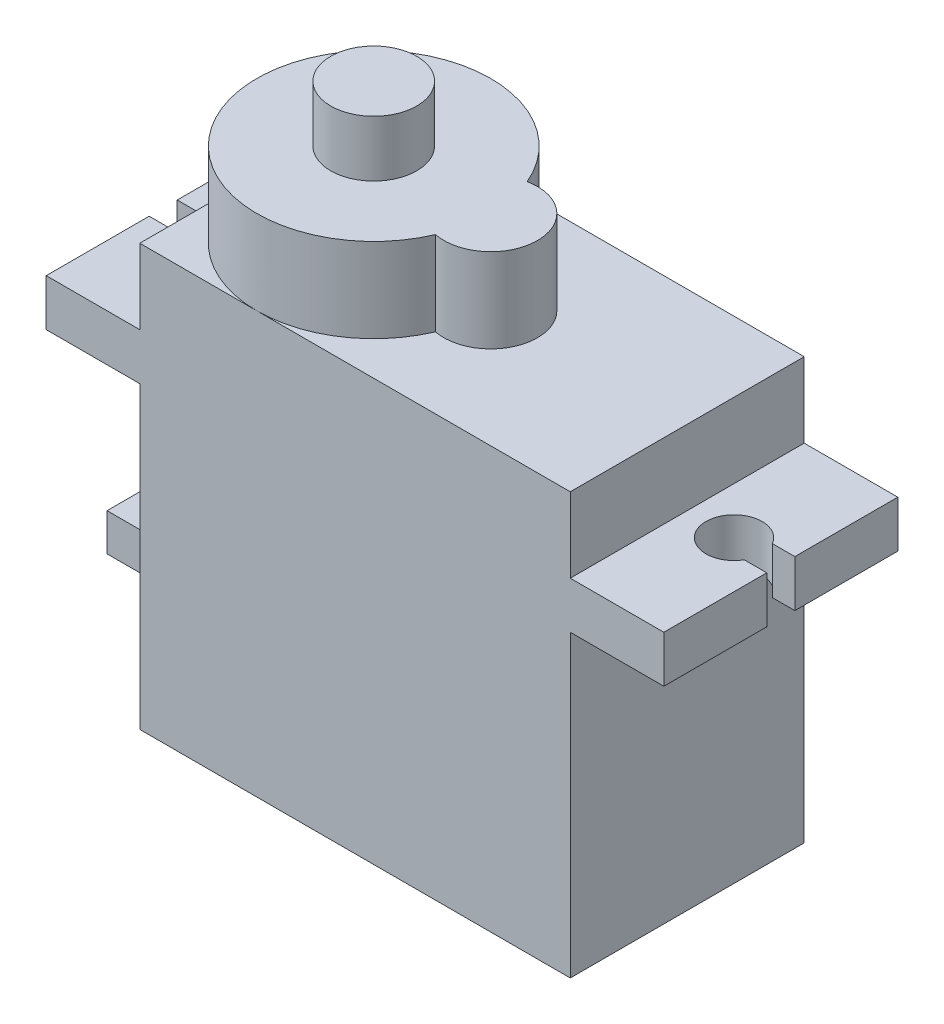
SolidWorks part; units mm, degrees
material "Custom Plastic"
ref_plane "Front Plane" through (0, 0, 0) normal (0, 0, 1) x (1, 0, 0)
ref_plane "Top Plane" through (0, 0, 0) normal (0, 1, 0) x (1, 0, 0)
ref_plane "Right Plane" through (0, 0, 0) normal (1, 0, 0) x (0, 0, -1)
sketch "Sketch1" plane through (0, 0, 0) normal (0, 1, 0) x (1, 0, 0)
  line L1 (11.5, -6.25) -> (-11.5, -6.25)
  line L2 (11.5, -6.25) -> (11.5, 6.25)
  line L3 (11.5, 6.25) -> (-11.5, 6.25)
  line L4 (-11.5, -6.25) -> (-11.5, 6.25)
  line L5 (11.5, -6.25) -> (-11.5, 6.25) construction
  line L6 (11.5, 6.25) -> (-11.5, -6.25) construction
  point P0 (0, 0)
  dimension "D1" = 12.5
  dimension "D2" = 23
extrude "Boss-Extrude1" add sketch "Sketch1" along normal blind 22.5
ref_plane "Plane1" through (0, 16, 0) normal (0, 1, 0) x (1, 0, 0)
sketch "Sketch2" plane through (0, 16, 0) normal (0, 1, 0) x (1, 0, 0)
  line L0 (11.5, 6.25) -> (16.5, 6.25)
  line L1 (-11.5, 6.25) -> (-11.5, -6.25) construction
  line L2 (0, 6.25) -> (0, -6.25) construction
  line L3 (-11.5, 6.25) -> (-11.5, -6.25)
  line L4 (-11.5, 6.25) -> (-16.5, 6.25)
  line L5 (-16.5, 6.25) -> (-16.5, 0.75)
  line L6 (-16.5, -0.75) -> (-16.5, -6.25)
  line L7 (-16.5, -6.25) -> (-11.5, -6.25)
  line L8 (-16.5, -0.75) -> (-15.299, -0.75)
  line L9 (-16.5, 0.75) -> (-15.299, 0.75)
  line L10 (-16.5, -0.75) -> (-16.5, 0.75) construction
  line L11 (11.5, 6.25) -> (-11.5, 6.25) construction
  line L12 (-11.5, -6.25) -> (11.5, -6.25) construction
  line L13 (16.5, 6.25) -> (16.5, 0.75)
  line L14 (16.5, 0.75) -> (15.299, 0.75)
  line L15 (16.5, -0.75) -> (15.299, -0.75)
  line L16 (16.5, -0.75) -> (16.5, -6.25)
  line L17 (16.5, -6.25) -> (11.5, -6.25)
  line L18 (11.5, 6.25) -> (11.5, -6.25)
  arc A2 (-15.299, -0.75) -> (-15.299, 0.75) centre (-14, 0) ccw
  arc A3 (15.299, -0.75) -> (15.299, 0.75) centre (14, 0) cw
  point P8 (-16.5, 0)
  point P10 (-11.5, 0)
  point P11 (-14, 6.25)
  dimension "D2" = 3
  dimension "D1" = 5
  dimension "D3" = 1.5
extrude "Boss-Extrude2" add sketch "Sketch2" along normal blind 2.5
sketch "Sketch3" plane through (0, 22.5, 0) normal (0, 1, 0) x (1, 0, 0)
  line L0 (-11.5, 6.25) -> (-11.5, -6.25) construction
  line L1 (11.5, 6.25) -> (-11.5, 6.25) construction
  arc A0 (0.5, 2.4495) -> (0.5, -2.4495) centre (-5.25, 0) ccw
  arc A1 (0.5, -2.4495) -> (0.5, 2.4495) centre (1, 0) ccw
  dimension "D1" = 5
extrude "Boss-Extrude3" add sketch "Sketch3" along normal blind 4.5
sketch "Sketch4" plane through (0, 27, 0) normal (0, 1, 0) x (1, 0, 0)
  circle A0 centre (-5.25, 0) radius 2.3
  dimension "D1" = 4.6
extrude "Boss-Extrude4" add sketch "Sketch4" along normal blind 3
sketch "Sketch6" plane through (-11.5, 0, 0) normal (-1, 0, 0) x (0, 0, 1)
  line L0 (-6.25, 0) -> (6.25, 0) construction
  line L1 (3, 4) -> (-3, 4)
  line L2 (3, 4) -> (3, 6)
  line L3 (3, 6) -> (-3, 6)
  line L4 (-3, 4) -> (-3, 6)
  line L5 (3, 4) -> (-3, 6) construction
  line L6 (3, 6) -> (-3, 4) construction
  point P0 (0, 5)
  point P7 (0, 0)
  dimension "D1" = 6
  dimension "D2" = 2
  dimension "D3" = 4
extrude "Boss-Extrude6" add sketch "Sketch6" along normal blind 5 contours L1 L4 L3 L2
